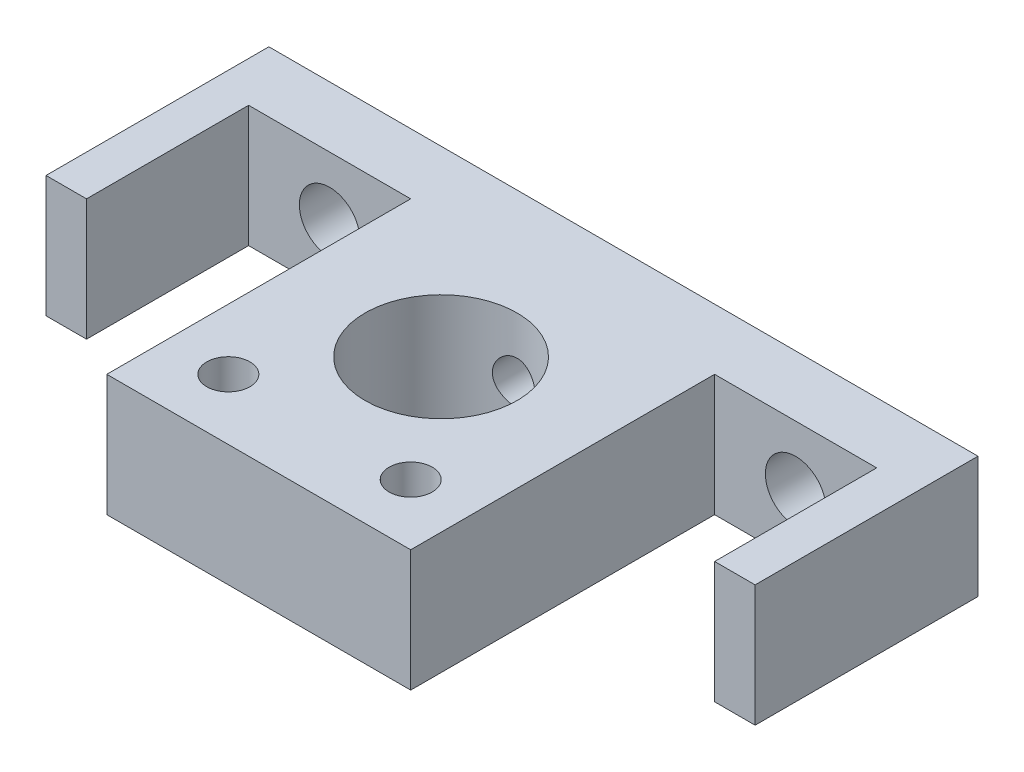
SolidWorks part; units mm, degrees
ref_plane "Front Plane" through (0, 0, 0) normal (0, 0, 1) x (1, 0, 0)
ref_plane "Top Plane" through (0, 0, 0) normal (0, 1, 0) x (1, 0, 0)
ref_plane "Right Plane" through (0, 0, 0) normal (1, 0, 0) x (0, 0, -1)
sketch "Sketch1" plane through (0, 0, 0) normal (0, 1, 0) x (1, 0, 0)
  line L21 (-22.225, -11.43) -> (22.225, -11.43)
  line L22 (-22.225, -11.43) -> (-22.225, 11.43)
  line L23 (-22.225, 11.43) -> (22.225, 11.43)
  line L24 (22.225, -11.43) -> (22.225, 11.43)
  line L25 (-22.225, -11.43) -> (22.225, 11.43) construction
  line L26 (-22.225, 11.43) -> (22.225, -11.43) construction
  circle A5 centre (0, 0) radius 4.7625
  dimension "D1" = 9.525
  dimension "D2" = 44.45
  dimension "D3" = 22.86
extrude "Boss-Extrude1" add sketch "Sketch1" along normal blind 7.62
sketch "Sketch2" plane through (0, 0, -11.43) normal (0, 0, -1) x (-1, 0, 0)
  line L3 (0, 55) -> (0, -55) construction
  line L4 (-22.225, 7.62) -> (-22.225, 0) construction
  point P0 (0, 3.81)
  point P8 (-22.225, 3.81)
hole_wizard "#6-32 Tapped Hole1" positions "Sketch3" profile "Sketch4" tap size "#6-32" standard "ANSI Inch"
sketch "Sketch3" plane through (0, 0, -11.43) normal (0, 0, -1) x (-1, 0, 0)
  point P0 (0, 3.81)
sketch "Sketch4" plane through (0, 3.81, -11.43) normal (1, 0, 0) x (0, 1, 0)
  line L0 (0, 0) -> (0, 6.6675)
  line L1 (0, 6.6675) -> (1.3525, 6.6675)
  line L2 (1.3525, 6.6675) -> (1.3525, 0)
  line L5 (1.3525, 0) -> (0, 0)
  line L11 (0, -6.35) -> (0, 107.95) construction
  dimension "Thru Tap Drill Dia." = 2.7051
  dimension "Thru Tap Drill Depth" = 6.6675
cosmetic thread "Hole Thread7" parameters "D2"=3.5052
sketch "Sketch5" [suppressed] plane through (9.525, 0, 0) normal (1, 0, 0) x (0, 0, -1)
  line L0 (0, 55) -> (0, -55) construction
  point P0 (0, 3.175)
hole_wizard "#6-32 Tapped Hole2" [suppressed] positions "Sketch6" profile "Sketch7" tap size "#6-32" standard "ANSI Inch"
sketch "Sketch6" [suppressed] plane through (9.525, 0, 0) normal (1, 0, 0) x (0, 0, -1)
  point P0 (0, 3.175)
sketch "Sketch7" plane through (9.525, 3.175, 0) normal (0, 1, 0) x (0, 0, -1)
  line L0 (0, 0) -> (0, 4.7625)
  line L1 (0, 4.7625) -> (1.3525, 4.7625)
  line L2 (1.3525, 4.7625) -> (1.3525, 0)
  line L5 (1.3525, 0) -> (0, 0)
  line L11 (0, -6.35) -> (0, 107.95) construction
  dimension "Thru Tap Drill Dia." = 2.7051
  dimension "Thru Tap Drill Depth" = 4.7625
cosmetic thread "Hole Thread2" [suppressed] parameters "D2"=3.5052
sketch "Sketch8" [suppressed] plane through (9.525, 0, 0) normal (1, 0, 0) x (0, 0, -1)
  line L0 (-9.525, 6.35) -> (-9.525, 0) construction
  point P0 (-5.715, 3.175)
  point P5 (-9.525, 3.175)
  dimension "D1" = 3.81
hole_wizard "#6-32 Tapped Hole3" [suppressed] positions "Sketch9" profile "Sketch11" tap size "#6-32" standard "ANSI Inch"
sketch "Sketch9" [suppressed] plane through (9.525, 0, 0) normal (1, 0, 0) x (0, 0, -1)
  point P0 (-5.715, 3.175)
sketch "Sketch11" plane through (9.525, 3.175, 5.715) normal (0, 1, 0) x (0, 0, -1)
  line L0 (0, 0) -> (0, 6.35)
  line L1 (0, 6.35) -> (1.3525, 5.5373)
  line L2 (1.3525, 5.5373) -> (1.3525, 0)
  line L5 (1.3525, 0) -> (0, 0)
  line L10 (0, 6.35) -> (-1.3526, 5.5373) construction
  line L11 (0, -6.35) -> (0, 107.95) construction
  dimension "Tap Drill Dia." = 2.7051
  dimension "Tap Drill Depth" = 6.35
  dimension "Drill Angle" = 118
cosmetic thread "Hole Thread3" [suppressed] parameters "D1"=5.588, "D2"=3.5052
mirror "Mirror1" [suppressed] about plane through (0, 0, 0) normal (0, 0, 1)
cosmetic thread "Hole Thread4" [suppressed] parameters "D1"=5.588, "D2"=3.5052
mirror "Mirror2" [suppressed] about plane through (0, 0, 0) normal (1, 0, 0)
cosmetic thread "Hole Thread5" [suppressed] parameters "D1"=5.588, "D2"=3.5052
cosmetic thread "Hole Thread6" [suppressed] parameters "D1"=5.588, "D2"=3.5052
sketch "Sketch15" plane through (0, 0, 11.43) normal (0, 0, 1) x (1, 0, 0)
  line L0 (22.225, 7.62) -> (22.225, 0) construction
  line L1 (9.525, 2.2225) -> (22.225, 2.2225)
  line L2 (9.525, 2.2225) -> (9.525, 5.3975)
  line L3 (9.525, 5.3975) -> (22.225, 5.3975)
  line L4 (22.225, 2.2225) -> (22.225, 5.3975)
  line L5 (9.525, 2.2225) -> (22.225, 5.3975) construction
  line L6 (9.525, 5.3975) -> (22.225, 2.2225) construction
  point P0 (15.875, 3.81)
  dimension "D1" = 3.175
  dimension "D2" = 12.7
extrude "Cut-Extrude1" [suppressed] cut sketch "Sketch15" against normal through all
sketch "Sketch12" [suppressed] plane through (0, 6.35, 0) normal (0, 1, 0) x (1, 0, 0)
  line L0 (15.875, 5.08) -> (15.875, -5.08) construction
  line L3 (-3.4925, 0) -> (3.4925, 0) construction
  line L4 (22.225, 9.525) -> (22.225, -9.525) construction
  line L5 (22.225, 9.525) -> (-22.225, 9.525) construction
  point P0 (15.875, 5.08)
  point P1 (15.875, -5.08)
  point P4 (15.875, 0)
  dimension "D1" = 6.35
  dimension "D2" = 10.16
hole_wizard "#6 (0.204) Diameter Hole1" [suppressed] positions "Sketch13" profile "Sketch14" hole size "#6" standard "ANSI Inch"
sketch "Sketch13" [suppressed] plane through (0, 6.35, 0) normal (0, 1, 0) x (1, 0, 0)
  point P0 (15.875, 5.08)
  point P3 (15.875, -5.08)
sketch "Sketch14" plane through (15.875, 6.35, -5.08) normal (1, 0, 0) x (0, 0, 1)
  line L0 (0, 0) -> (0, 1.5875)
  line L1 (0, 1.5875) -> (2.5908, 1.5875)
  line L2 (2.5908, 1.5875) -> (2.5908, 0)
  line L5 (2.5908, 0) -> (0, 0)
  line L11 (0, -6.35) -> (0, 107.95) construction
  dimension "Thru Hole Dia." = 5.1816
  dimension "Thru Hole Depth" = 1.5875
hole_wizard "#6-32 Tapped Hole4" [suppressed] positions "Sketch16" profile "Sketch18" tap size "#6-32" standard "ANSI Inch"
sketch "Sketch16" [suppressed] plane through (0, 1.5875, 0) normal (0, 1, 0) x (1, 0, 0)
  point P0 (15.875, 5.08)
  point P3 (15.875, -5.08)
sketch "Sketch18" plane through (15.875, 1.5875, -5.08) normal (1, 0, 0) x (0, 0, 1)
  line L0 (0, 0) -> (0, 1.5875)
  line L1 (0, 1.5875) -> (1.3525, 1.5875)
  line L2 (1.3525, 1.5875) -> (1.3525, 0)
  line L5 (1.3525, 0) -> (0, 0)
  line L11 (0, -6.35) -> (0, 107.95) construction
  dimension "Thru Tap Drill Dia." = 2.7051
  dimension "Thru Tap Drill Depth" = 1.5875
cosmetic thread "Hole Thread8" [suppressed] parameters "D2"=3.5052
cosmetic thread "Hole Thread9" [suppressed] parameters "D2"=3.5052
mirror "Mirror3" [suppressed] about plane through (0, 0, 0) normal (1, 0, 0)
cosmetic thread "Hole Thread10" [suppressed] parameters "D2"=3.5052
cosmetic thread "Hole Thread11" [suppressed] parameters "D2"=3.5052
sketch "Sketch19" plane through (0, 7.62, 0) normal (0, 1, 0) x (1, 0, 0)
  line L0 (22.225, 11.43) -> (-22.225, 11.43) construction
  line L1 (-22.225, -11.43) -> (-9.525, -11.43)
  line L2 (-22.225, -11.43) -> (-22.225, 7.62)
  line L3 (-22.225, 7.62) -> (-9.525, 7.62)
  line L4 (-9.525, -11.43) -> (-9.525, 7.62)
  dimension "D1" = 3.81
  dimension "D2" = 12.7
extrude "Cut-Extrude2" cut sketch "Sketch19" against normal up to next
sketch "Sketch20" plane through (0, 0, -7.62) normal (0, 0, 1) x (1, 0, 0)
  line L1 (-22.225, 0) -> (-22.225, 7.62) construction
  line L2 (-9.525, 0) -> (-9.525, 7.62) construction
  point P0 (-14.605, 3.81)
  point P6 (-22.225, 3.81)
  dimension "D1" = 5.08
hole_wizard "#6 Clearance Hole1" positions "Sketch21" profile "Sketch23" hole size "#6" standard "ANSI Inch" end condition up to next
sketch "Sketch21" plane through (0, 0, -7.62) normal (0, 0, 1) x (1, 0, 0)
  point P0 (-14.605, 3.81)
sketch "Sketch23" plane through (-14.605, 3.81, -7.62) normal (1, 0, 0) x (0, -1, 0)
  line L0 (0, 0) -> (0, 3.81)
  line L1 (0, 3.81) -> (1.8986, 3.81)
  line L2 (1.8986, 3.81) -> (1.8986, 0)
  line L5 (1.8986, 0) -> (0, 0)
  line L11 (0, -6.35) -> (0, 107.95) construction
  dimension "Thru Hole Dia." = 3.7973
  dimension "Thru Hole Depth" = 3.81
mirror "Mirror4" about plane through (0, 0, 0) normal (1, 0, 0) of "#6 Clearance Hole1", "Cut-Extrude2"
sketch "Sketch24" plane through (0, 0, -7.62) normal (0, 0, 1) x (1, 0, 0)
  line L0 (-9.525, 0) -> (-22.225, 0) construction
  line L1 (-22.225, 7.62) -> (-19.685, 7.62)
  line L2 (-22.225, 7.62) -> (-22.225, 0)
  line L3 (-22.225, 0) -> (-19.685, 0)
  line L4 (-19.685, 7.62) -> (-19.685, 0)
  dimension "D1" = 2.54
extrude "Boss-Extrude2" add sketch "Sketch24" along normal blind 10.16
mirror "Mirror5" about plane through (0, 0, 0) normal (1, 0, 0) of "Boss-Extrude2"
sketch "Sketch25" plane through (0, 7.62, 0) normal (0, 1, 0) x (1, 0, 0)
  line L0 (-5.715, -7.62) -> (5.715, -7.62) construction
  line L1 (0, -4.191) -> (0, 4.191) construction
  line L2 (-9.525, -11.43) -> (9.525, -11.43) construction
  line L3 (9.525, -11.43) -> (9.525, 7.62) construction
  point P0 (-5.715, -7.62)
  point P1 (5.715, -7.62)
  point P4 (0, -7.62)
  dimension "D1" = 3.81
  dimension "D2" = 3.81
hole_wizard "#6-32 Tapped Hole5" positions "Sketch26" profile "Sketch28" tap size "#6-32" standard "ANSI Inch" end condition through all
sketch "Sketch26" plane through (0, 7.62, 0) normal (0, 1, 0) x (1, 0, 0)
  point P0 (-5.715, -7.62)
  point P3 (5.715, -7.62)
cosmetic thread "Hole Thread12" parameters "D2"=3.5052
cosmetic thread "Hole Thread13" parameters "D2"=3.5052
sketch "Sketch28" plane through (-5.715, 7.62, 7.62) normal (1, 0, 0) x (0, 0, 1)
  line L0 (0, 0) -> (0, 7.62)
  line L1 (0, 7.62) -> (1.3525, 7.62)
  line L2 (1.3525, 7.62) -> (1.3525, 0)
  line L5 (1.3525, 0) -> (0, 0)
  line L11 (0, -6.35) -> (0, 107.95) construction
  dimension "Thru Tap Drill Dia." = 2.7051
  dimension "Thru Tap Drill Depth" = 7.62
